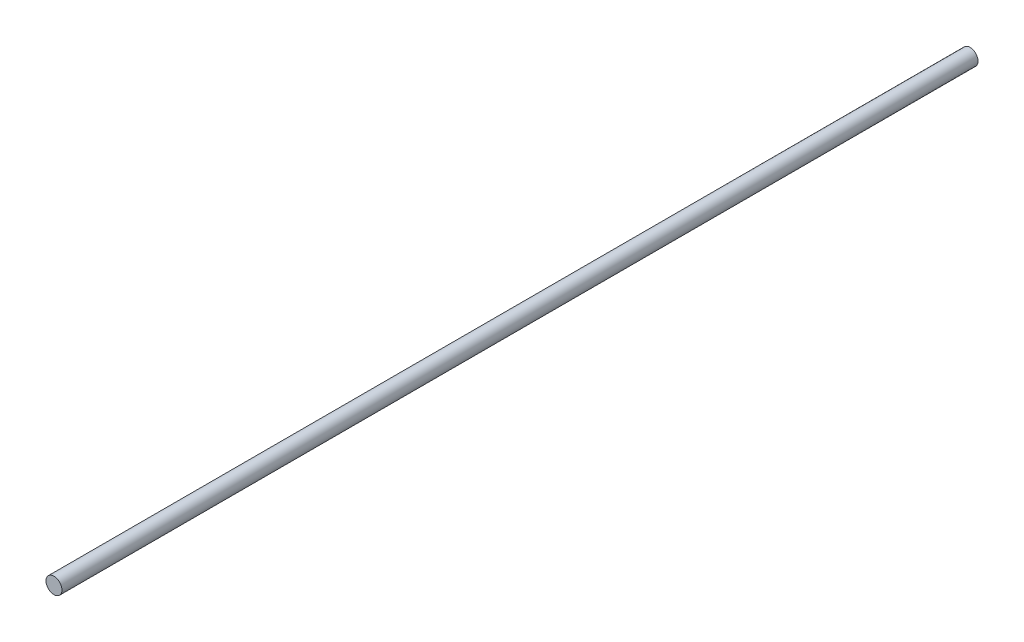
SolidWorks part; units mm, degrees
ref_plane "Front" through (0, 0, 0) normal (0, 0, 1) x (1, 0, 0)
ref_plane "Top" through (0, 0, 0) normal (0, 1, 0) x (1, 0, 0)
ref_plane "Right" through (0, 0, 0) normal (1, 0, 0) x (0, 0, -1)
sketch "草图1" plane through (0, 0, 0) normal (0, 0, 1) x (1, 0, 0)
  circle A0 centre (0, 0) radius 1.5
extrude "凸台-拉伸1" add sketch "草图1" along normal blind 172
